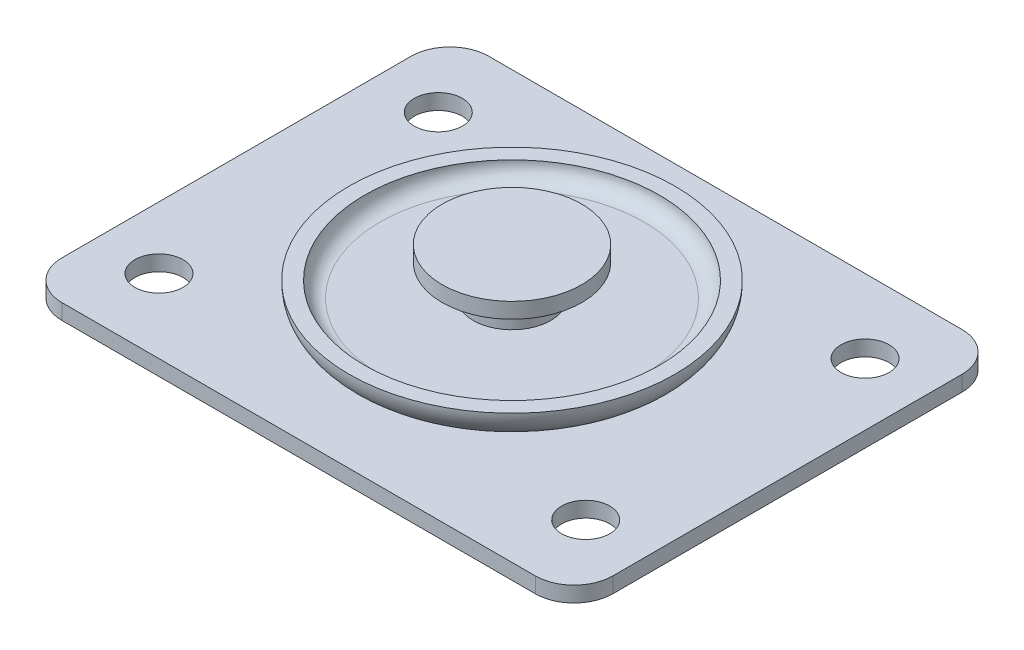
SolidWorks part; units mm, degrees
ref_plane "前视基准面" through (0, 0, 0) normal (0, 0, 1) x (1, 0, 0)
ref_plane "上视基准面" through (0, 0, 0) normal (0, 1, 0) x (1, 0, 0)
ref_plane "右视基准面" through (0, 0, 0) normal (1, 0, 0) x (0, 0, -1)
other "Configuration Table"
ref_plane "基准面1" through (0, 0, 0) normal (0, 0, -1) x (-1, 0, 0)
sketch "草图1" plane through (0, 0, 0) normal (0, 0, -1) x (-1, 0, 0)
  line L0 (-17, -2) -> (0, -2)
  line L1 (0, -2) -> (0, 0)
  line L2 (0, 0) -> (-17, 0)
  line L3 (-19, 2) -> (-21, 2)
  line L4 (0, -2.005) -> (0, 2) construction
  arc A0 (-17, 0) -> (-19, 2) centre (-17, 2) cw
  arc A1 (-21, 2) -> (-17, -2) centre (-17, 2) ccw
revolve "旋转1" add sketch "草图1" angle 360 about L4
ref_plane "基准面2" through (0, -2, 0) normal (0, 1, 0) x (1, 0, 0)
sketch "草图2" plane through (0, -2, 0) normal (0, 1, 0) x (1, 0, 0)
  line L0 (35.5, 27.5) -> (-35.5, 27.5)
  line L1 (-35.5, 27.5) -> (-35.5, -27.5)
  line L2 (-35.5, -27.5) -> (35.5, -27.5)
  line L3 (35.5, -27.5) -> (35.5, 27.5)
extrude "凸台-拉伸1" add sketch "草图2" against normal blind 2
sketch "草图3" plane through (0, 0, 0) normal (0, 0, -1) x (-1, 0, 0)
  line L0 (-5, 0) -> (0, 0)
  line L1 (0, 0) -> (0, 6)
  line L2 (0, 6) -> (-9, 6)
  line L3 (-9, 6) -> (-9, 4)
  line L4 (-9, 4) -> (-5, 4)
  line L5 (-5, 4) -> (-5, 0)
  line L6 (0, 0) -> (0, 6) construction
revolve "旋转2" add sketch "草图3" angle 360 about L6
hole_wizard "Ø6.2 (6.2) 直径孔1" positions "草图5" profile "草图4" hole size "Ø6.2" standard "ANSI Metric"
sketch "草图5" plane through (0, -2, 0) normal (0, 1, 0) x (1, 0, 0)
  point P0 (-27.5, 18)
  point P1 (-27.5, -18)
  point P2 (27.5, -18)
  point P3 (27.5, 18)
sketch "草图4" plane through (-27.5, -2, -18) normal (1, 0, 0) x (0, 0, 1)
  line L0 (0, 0) -> (0, 2)
  line L1 (0, 2) -> (3.1, 2)
  line L2 (3.1, 2) -> (3.1, 0)
  line L5 (3.1, 0) -> (0, 0)
  line L11 (0, -6.35) -> (0, 107.95) construction
  dimension "通孔孔直径" = 6.2
  dimension "通孔孔深度" = 2
fillet "圆角1" radius 5 4 edges at (35.5, -3, -27.5) (35.5, -3, 27.5) (-35.5, -3, 27.5) (-35.5, -3, -27.5)
